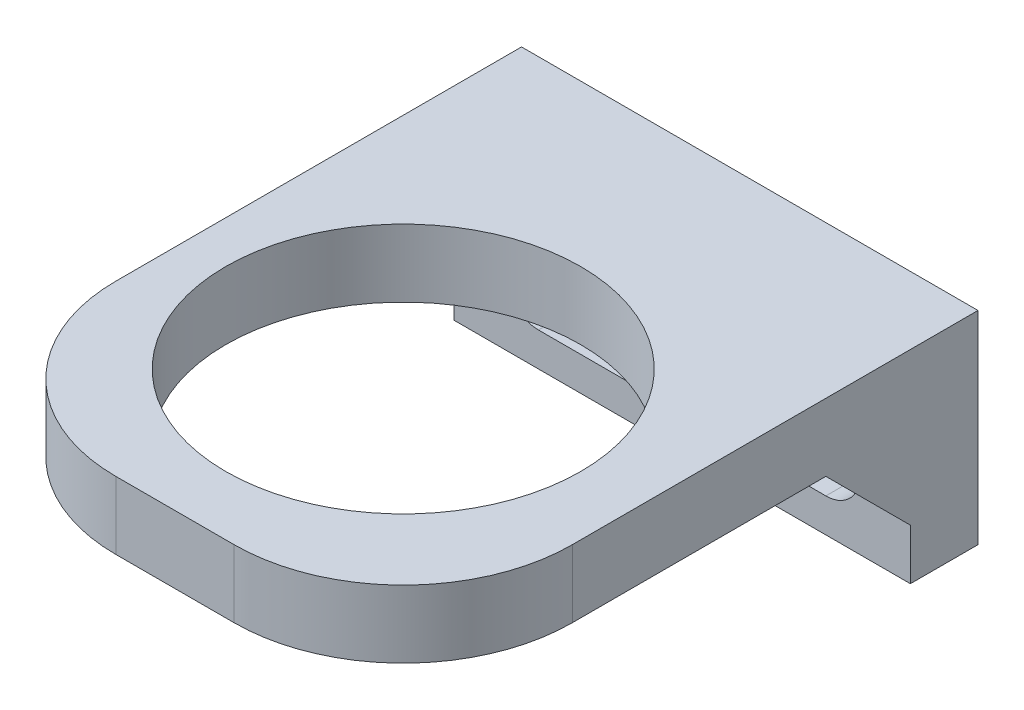
SolidWorks part; units mm, degrees
ref_plane "Plan de face" through (0, 0, 0) normal (0, 0, 1) x (1, 0, 0)
ref_plane "Plan de dessus" through (0, 0, 0) normal (0, 1, 0) x (1, 0, 0)
ref_plane "Plan de droite" through (0, 0, 0) normal (1, 0, 0) x (0, 0, -1)
sketch "Esquisse1" plane through (0, 0, 0) normal (0, 1, 0) x (1, 0, 0)
  line L1 (-13, 20) -> (14, 20)
  line L2 (-13, 20) -> (-13, -14)
  line L3 (-13, -14) -> (14, -14)
  line L4 (14, 20) -> (14, -14)
  line L6 (-13, 0) -> (14, 0) construction
  circle A0 centre (0, 0) radius 10.5
  dimension "D1" = 21
  dimension "D2" = 27
  dimension "D3" = 34
  dimension "D4" = 14
  dimension "D5" = 13
extrude "Boss.-Extru.1" add sketch "Esquisse1" along normal blind 4
sketch "Esquisse2" plane through (0, 0, 0) normal (0, -1, 0) x (1, 0, 0)
  line L0 (14, 14) -> (14, -20) construction
  line L1 (-13, -20) -> (14, -20)
  line L2 (-13, -20) -> (-13, -16)
  line L3 (-13, -16) -> (14, -16)
  line L4 (14, -20) -> (14, -16)
  dimension "D1" = 4
extrude "Boss.-Extru.2" add sketch "Esquisse2" along normal blind 8
sketch "Esquisse5" plane through (-13, 0, 0) normal (-1, 0, 0) x (0, 0, 1)
  line L0 (-16, 0) -> (-16, -5)
  line L1 (-16, -8) -> (-16, 0) construction
  line L2 (-16, -5) -> (-11, 0)
  line L3 (-16, 0) -> (14, 0) construction
  line L4 (-11, 0) -> (-16, 0)
  dimension "D1" = 45
  dimension "D2" = 5
extrude "Boss.-Extru.3" add sketch "Esquisse5" against normal blind 2
sketch "Esquisse6" plane through (14, 0, 0) normal (1, 0, 0) x (0, 0, -1)
  line L0 (16, 0) -> (11, 0)
  line L1 (-14, 0) -> (16, 0) construction
  line L2 (11, 0) -> (16, -5)
  line L3 (16, -8) -> (16, 0) construction
  line L4 (16, -5) -> (16, 0)
  dimension "D1" = 45
  dimension "D2" = 5
extrude "Boss.-Extru.4" add sketch "Esquisse6" against normal blind 2
fillet "Congé1" radius 10 2 edges at (-13, 2, 14) (14, 2, 14)
sketch "Esquisse7" plane through (0, 0, -16) normal (0, 0, 1) x (1, 0, 0)
  line L0 (-8, -4) -> (9, -4) construction
  line L1 (-8, -2) -> (9, -2)
  line L2 (-8, -6) -> (9, -6)
  line L3 (14, -8) -> (14, -5) construction
  line L4 (-13, -8) -> (-13, -5) construction
  line L5 (12, 0) -> (-11, 0) construction
  arc A0 (-8, -2) -> (-8, -6) centre (-8, -4) ccw
  arc A1 (9, -6) -> (9, -2) centre (9, -4) ccw
  point P2 (0.5, -4)
  dimension "D1" = 4
  dimension "D2" = 5
  dimension "D3" = 5
  dimension "D4" = 4
extrude "Enlèv. mat.-Extru.1" cut sketch "Esquisse7" against normal through all
